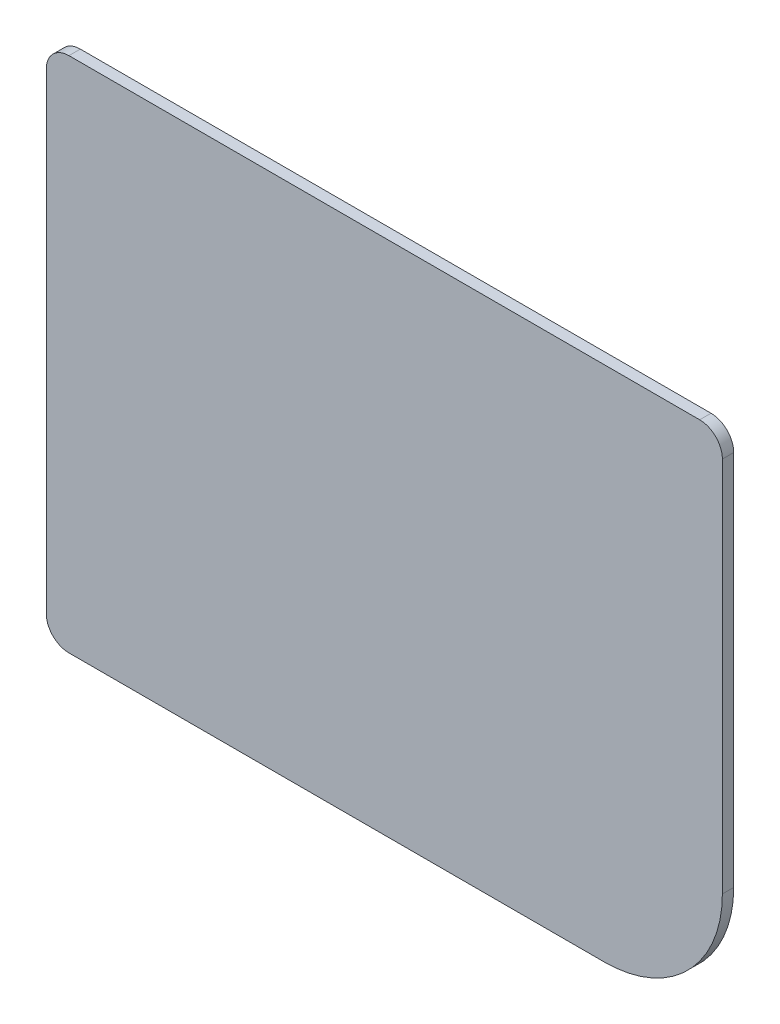
SolidWorks part; units mm, degrees
ref_plane "Front Plane" through (0, 0, 0) normal (0, 0, 1) x (1, 0, 0)
ref_plane "Top Plane" through (0, 0, 0) normal (0, 1, 0) x (1, 0, 0)
ref_plane "Right Plane" through (0, 0, 0) normal (1, 0, 0) x (0, 0, -1)
sketch "Sketch1" plane through (0, 0, 0) normal (0, 0, 1) x (1, 0, 0)
  line L1 (-34.75, -28.5) -> (24.25, -28.5)
  line L2 (-37.25, -26) -> (-37.25, 26)
  line L3 (-34.75, 28.5) -> (34.75, 28.5)
  line L4 (37.25, -15.5) -> (37.25, 26)
  line L5 (-37.25, -28.5) -> (37.25, 28.5) construction
  line L6 (-37.25, 28.5) -> (37.25, -28.5) construction
  arc A0 (24.25, -28.5) -> (37.25, -15.5) centre (24.25, -15.5) ccw
  arc A1 (-34.75, -28.5) -> (-37.25, -26) centre (-34.75, -26) cw
  arc A2 (-37.25, 26) -> (-34.75, 28.5) centre (-34.75, 26) cw
  arc A3 (34.75, 28.5) -> (37.25, 26) centre (34.75, 26) cw
  point P0 (0, 0)
  dimension "D3" = 13
  dimension "D4" = 2.5
  dimension "D1" = 74.5
  dimension "D2" = 57
extrude "Boss-Extrude1" add sketch "Sketch1" along normal blind 1.25
